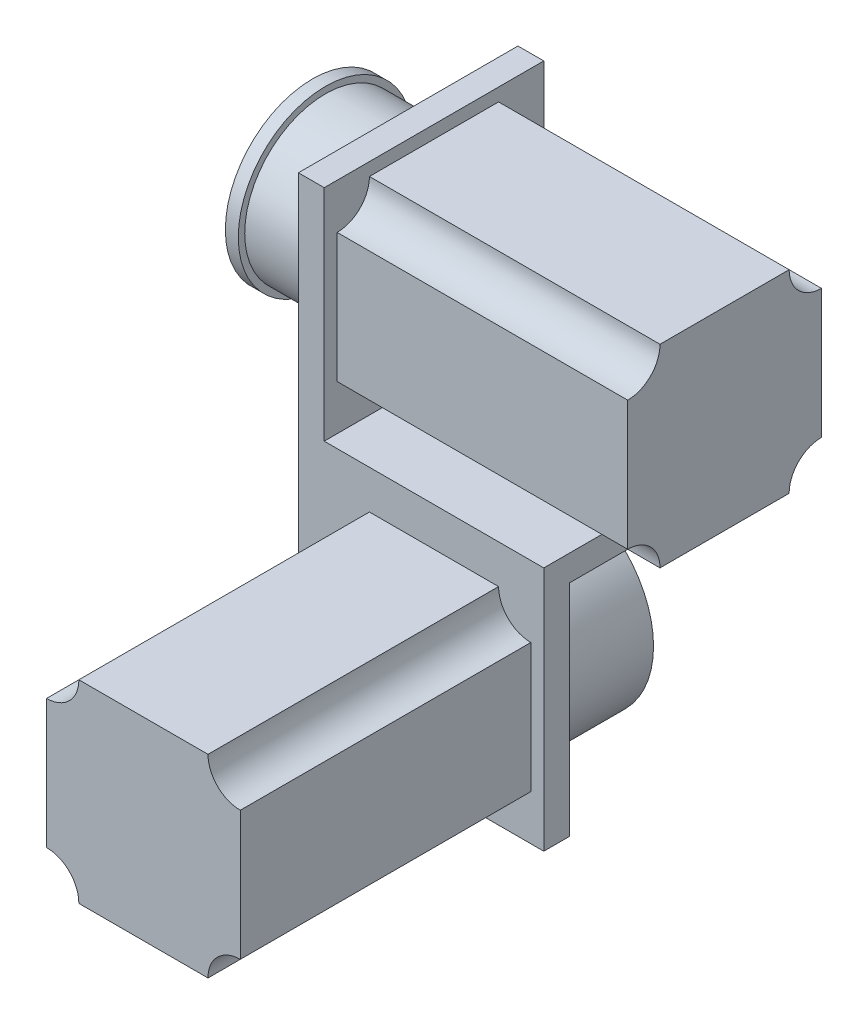
SolidWorks part; units mm, degrees
ref_plane "Front Plane" through (0, 0, 0) normal (0, 0, 1) x (1, 0, 0)
ref_plane "Top Plane" through (0, 0, 0) normal (0, 1, 0) x (1, 0, 0)
ref_plane "Right Plane" through (0, 0, 0) normal (1, 0, 0) x (0, 0, -1)
sketch "Sketch2" plane through (0, 0, 0) normal (0, 0, 1) x (1, 0, 0)
  line L0 (-40.3983, 30.2385) -> (-20.3983, 30.2385)
  line L11 (-20.3983, 30.2385) -> (-20.3983, -139.7615)
  line L12 (-20.3983, -139.7615) -> (149.6017, -139.7615)
  line L13 (149.6017, -139.7615) -> (149.6017, -159.7615)
  line L14 (149.6017, -159.7615) -> (-40.3983, -159.7615)
  line L15 (-40.3983, -159.7615) -> (-40.3983, 30.2385)
extrude "Boss-Extrude1" add sketch "Sketch2" against normal blind 170
sketch "Sketch3" plane through (-40.3983, 0, 0) normal (-1, 0, 0) x (0, 0, 1)
  circle A1 centre (-85.9385, -54.7615) radius 62.5
extrude "Boss-Extrude2" add sketch "Sketch3" along normal blind 75
sketch "Sketch4" plane through (-20.3983, 0, 0) normal (1, 0, 0) x (0, 0, -1)
  line L1 (10, 20.2385) -> (160, 20.2385)
  line L2 (10, 20.2385) -> (10, -129.7615)
  line L3 (10, -129.7615) -> (160, -129.7615)
  line L4 (160, 20.2385) -> (160, -129.7615)
extrude "Boss-Extrude3" add sketch "Sketch4" along normal blind 225
sketch "Sketch5" plane through (204.6017, 0, 0) normal (1, 0, 0) x (0, 0, -1)
  line L4 (10, 20.2385) -> (10, -129.7615)
  line L5 (10, -129.7615) -> (160, -129.7615)
  line L6 (160, -129.7615) -> (160, 20.2385)
  line L7 (160, 20.2385) -> (10, 20.2385)
  line L8 (10, 20.2385) -> (10, -129.7615)
  line L9 (10, -129.7615) -> (160, -129.7615)
  line L10 (160, -129.7615) -> (160, 20.2385)
  line L11 (160, 20.2385) -> (10, 20.2385)
  arc A4 (10, -4.7615) -> (35, 20.2385) centre (10, 20.2385) ccw
  arc A5 (135, 20.2385) -> (160, -4.7615) centre (160, 20.2385) ccw
  arc A6 (135, -129.7615) -> (160, -104.7615) centre (160, -129.7615) cw
  arc A7 (35, -129.7615) -> (10, -104.7615) centre (10, -129.7615) ccw
  line M1 (10, 20.2385) -> (10, -129.7615)
  line M2 (10, -129.7615) -> (160, -129.7615)
  line M3 (160, -129.7615) -> (160, 20.2385)
  line M4 (160, 20.2385) -> (10, 20.2385)
  dimension "D1" = 0
extrude "Cut-Extrude6" cut sketch "Sketch5" against normal up to surface (225 mm away) contours A4 L11 M1 | A7 M2 M1 | A6 L9 M3 | A5 L10 M4 up to face at (-20.3983, -54.7615, -85)
sketch "Sketch7" plane through (0, -159.7615, 0) normal (0, -1, 0) x (1, 0, 0)
  line L0 (149.6017, -170) -> (149.6017, 0) construction
  line L1 (-40.3983, 0) -> (149.6017, 0)
  line L2 (-40.3983, 0) -> (-40.3983, -20)
  line L3 (-40.3983, -20) -> (149.6017, -20)
  line L4 (149.6017, 0) -> (149.6017, -20)
  line L5 (-25.5226, -13.9744) -> (-24.7084, -13.9548)
extrude "Boss-Extrude5" add sketch "Sketch7" along normal blind 170
sketch "Sketch10" plane through (0, 0, 0) normal (0, 0, 1) x (1, 0, 0)
  line L1 (-10.3983, -169.7615) -> (139.6017, -169.7615)
  line L2 (-10.3983, -169.7615) -> (-10.3983, -319.7615)
  line L3 (-10.3983, -319.7615) -> (139.6017, -319.7615)
  line L4 (139.6017, -169.7615) -> (139.6017, -319.7615)
extrude "Boss-Extrude7" add sketch "Sketch10" along normal blind 225
sketch "Sketch11" plane through (0, 0, 225) normal (0, 0, 1) x (1, 0, 0)
  line L0 (139.6017, -169.7615) -> (-10.3983, -169.7615) construction
  line L1 (-10.3983, -169.7615) -> (-10.3983, -319.7615) construction
  line L2 (139.6017, -319.7615) -> (139.6017, -169.7615) construction
  line L3 (139.6017, -319.7615) -> (139.6017, -169.7615) construction
  line L4 (-10.3983, -319.7615) -> (139.6017, -319.7615) construction
  line L5 (-10.3983, -169.7615) -> (-10.3983, -319.7615) construction
  line L10 (-10.3983, -169.7615) -> (-10.3983, -319.7615)
  line L11 (-10.3983, -319.7615) -> (139.6017, -319.7615)
  line L12 (139.6017, -319.7615) -> (139.6017, -169.7615)
  line L13 (139.6017, -169.7615) -> (-10.3983, -169.7615)
  line L14 (-10.3983, -169.7615) -> (-10.3983, -319.7615)
  line L15 (-10.3983, -319.7615) -> (139.6017, -319.7615)
  line L16 (139.6017, -319.7615) -> (139.6017, -169.7615)
  line L17 (139.6017, -169.7615) -> (-10.3983, -169.7615)
  arc A0 (14.6017, -169.7615) -> (-10.3983, -194.7615) centre (-10.3983, -169.7615) cw
  arc A1 (114.6017, -169.7615) -> (139.6017, -194.7615) centre (139.6017, -169.7615) ccw
  arc A2 (139.6017, -294.7615) -> (114.6017, -319.7615) centre (139.6017, -319.7615) ccw
  arc A3 (14.6017, -319.7615) -> (-10.3983, -294.7615) centre (-10.3983, -319.7615) ccw
  line M5 (-10.3983, -169.7615) -> (-10.3983, -319.7615)
  line M6 (-10.3983, -319.7615) -> (139.6017, -319.7615)
  line M7 (139.6017, -319.7615) -> (139.6017, -169.7615)
  line M8 (139.6017, -169.7615) -> (-10.3983, -169.7615)
  dimension "D1" = 0
extrude "Cut-Extrude7" cut sketch "Sketch11" against normal up to surface (225 mm away) contours A0 L17 M5 | A1 L16 M8 | A2 L15 M7 | A3 M6 M5 up to face at (29.6017, -146.4282, 0)
sketch "Sketch12" plane through (0, 0, -20) normal (0, 0, -1) x (-1, 0, 0)
  circle A0 centre (-64.6017, -244.7615) radius 75
  circle A1 centre (-64.6017, -244.7615) radius 62.5
extrude "Boss-Extrude8" add sketch "Sketch12" along normal blind 75
sketch "Sketch13" plane through (-115.3983, 0, 0) normal (-1, 0, 0) x (0, 0, 1)
  circle A0 centre (-85.9385, -54.7615) radius 67.5
  circle A1 centre (-85.9385, -54.7615) radius 62.5
  circle A2 centre (-85.9385, -54.7615) radius 62.5
  dimension "D2" = 5
  dimension "D1" = 0
extrude "Boss-Extrude9" add sketch "Sketch13" against normal blind 10
ref_axis "Axis1" through (64.6017, -244.7615, -95) along (0, 0, 1)
ref_plane "Plane1" through (64.6017, 0, 0) normal (1, 0, 0) x (0, 0, -1)
sketch "Sketch14" plane through (64.6017, 0, 0) normal (1, 0, 0) x (0, 0, -1)
  line L4 (20, -329.7615) -> (20, -159.7615) construction
  line L5 (30, -177.2615) -> (20, -177.2615)
  line L6 (30, -177.2615) -> (30, -191.3002)
  line L7 (30, -191.3002) -> (20, -191.3002)
  line L8 (20, -177.2615) -> (20, -191.3002)
  dimension "D2" = 10
revolve "Cut-Revolve1" cut sketch "Sketch14" angle 360 about axis through (64.6017, -244.7615, -95) along (0, 0, 1)
